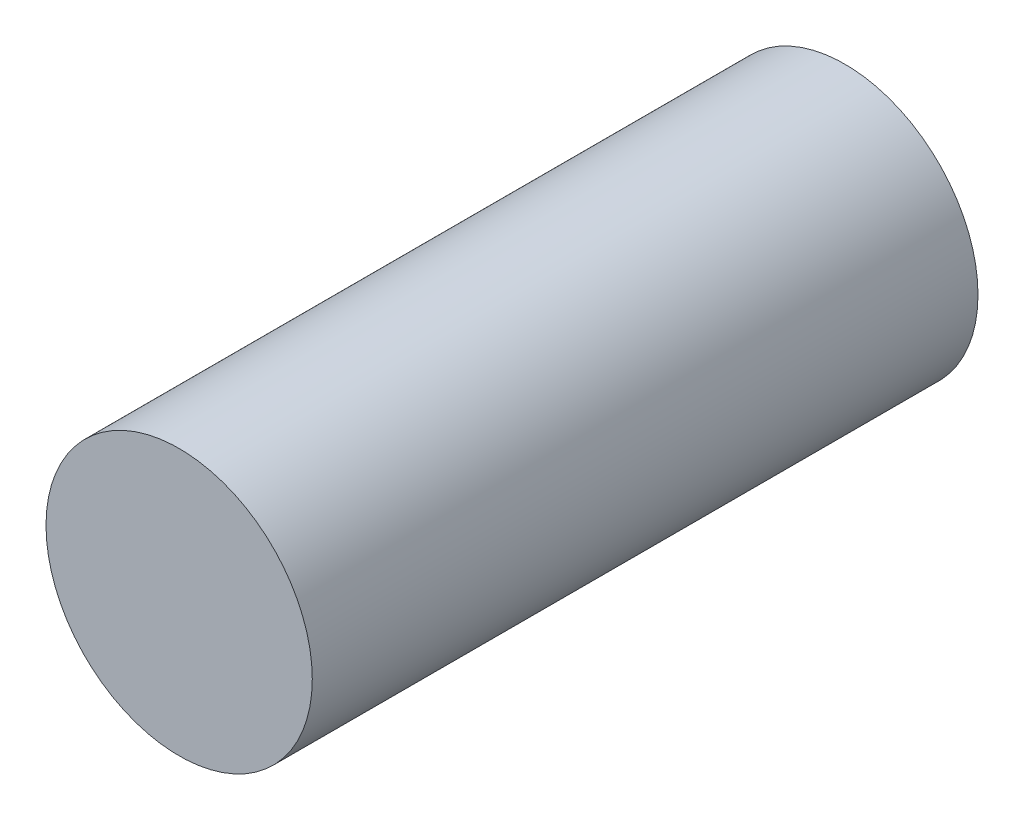
SolidWorks part; units mm, degrees
ref_plane "Front Plane" through (0, 0, 0) normal (0, 0, 1) x (1, 0, 0)
ref_plane "Top Plane" through (0, 0, 0) normal (0, 1, 0) x (1, 0, 0)
ref_plane "Right Plane" through (0, 0, 0) normal (1, 0, 0) x (0, 0, -1)
other "Configuration Table"
sketch "Sketch1" plane through (0, 0, 0) normal (0, 0, 1) x (1, 0, 0)
  circle A0 centre (460, 1334) radius 4
extrude "TOPPING_kat2_kapak_pimi_D8_2" add sketch "Sketch1" against normal blind 20 from offset 40 separate body
